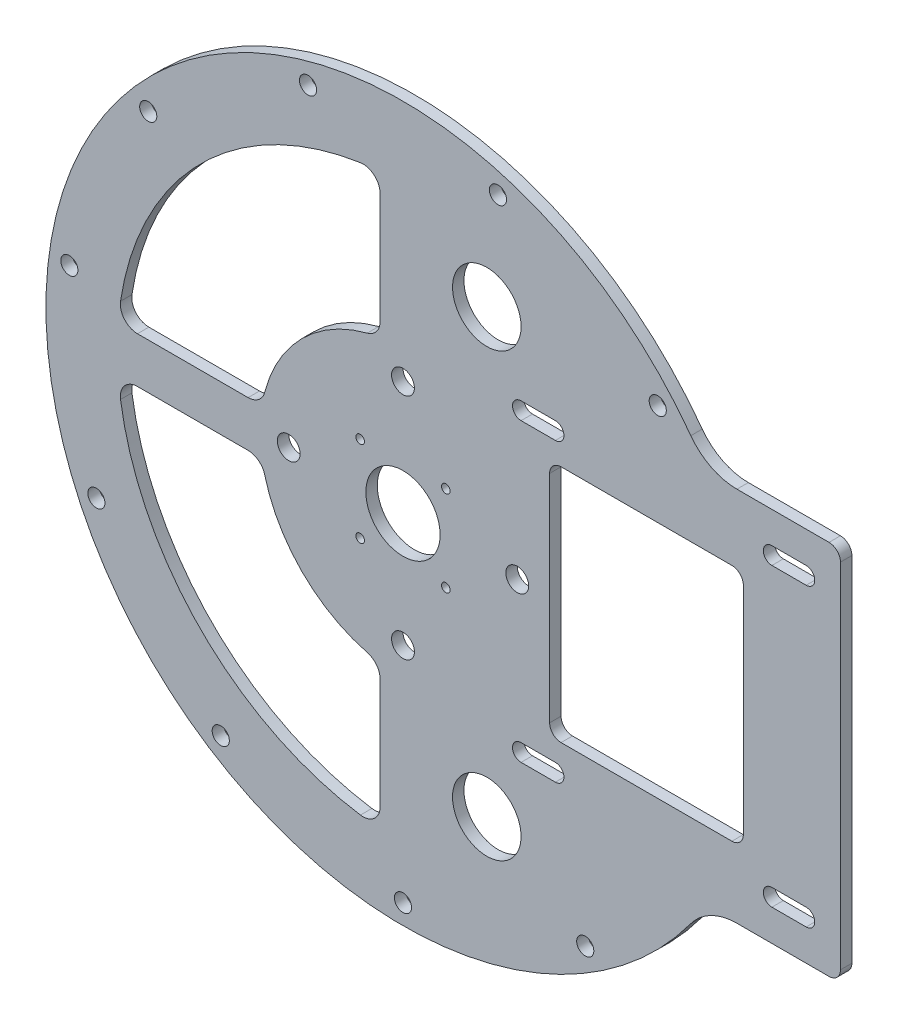
SolidWorks part; units mm, degrees
ref_plane "前视基准面" through (0, 0, 0) normal (0, 0, 1) x (1, 0, 0)
ref_plane "上视基准面" through (0, 0, 0) normal (0, 1, 0) x (1, 0, 0)
ref_plane "右视基准面" through (0, 0, 0) normal (1, 0, 0) x (0, 0, -1)
sketch "草图1" plane through (0, 0, 0) normal (0, 0, 1) x (1, 0, 0)
  line L0 (0, 0) -> (-27.6423, -27.6423) construction
  line L1 (0, 0) -> (0, -5.1352) construction
  line L2 (0, 0) -> (-102.4397, 0) construction
  line L3 (0, 1.2542) -> (0, 77.8801) construction
  line L4 (0, 0) -> (118.6635, 0) construction
  line L5 (0, 0) -> (0, -124.4057) construction
  line L6 (-46.4758, 4) -> (-27.1109, 4)
  line L8 (-27.1109, -4) -> (-46.4758, -4)
  line L9 (-4, 27.1109) -> (-4, 46.4758)
  line L12 (-4, -46.4758) -> (-4, -27.1109)
  line L14 (46.4758, -4) -> (27.1109, -4) [skipped]
  line L15 (4, -27.1109) -> (4, -46.4758) [skipped]
  line L16 (27.1109, 4) -> (46.4758, 4) [skipped]
  line L17 (4, 46.4758) -> (4, 27.1109) [skipped]
  line L19 (-14.6685, -17.526) -> (-14.6685, 17.526) construction
  line L20 (-14.6685, -17.526) -> (14.6685, -17.526) construction
  line L21 (14.6685, -17.526) -> (14.6685, 17.526) construction
  line L22 (-14.6685, 17.526) -> (14.6685, 17.526) construction
  line L24 (0, 0) -> (33.5645, 1.0745) construction
  line L25 (0, 0) -> (30.8589, 32.9) construction
  line L26 (14.6685, -9.5748) -> (14.6685, 9.5914) construction
  line L27 (-14.6685, -9.5748) -> (-14.6685, 9.5914) construction
  line L28 (14.6685, 28.961) -> (14.6685, -32.7618) construction
  line L29 (20.6685, 25.9) -> (64.5685, 25.9) construction
  line L30 (20.6685, 25.9) -> (20.6685, -25.9) construction
  line L31 (20.6685, -25.9) -> (64.5685, -25.9) construction
  line L32 (64.5685, 25.9) -> (64.5685, -25.9) construction
  line L33 (20.6685, -25.9) -> (26.6685, -25.9) construction
  line L34 (20.6685, -24.4) -> (26.6685, -24.4)
  line L35 (20.6685, -27.4) -> (26.6685, -27.4)
  line L36 (20.6685, 25.9) -> (26.6685, 25.9) construction
  line L37 (20.6685, 27.4) -> (26.6685, 27.4)
  line L38 (20.6685, 24.4) -> (26.6685, 24.4)
  line L39 (64.5685, 25.9) -> (70.5685, 25.9) construction
  line L40 (64.5685, 27.4) -> (70.5685, 27.4)
  line L41 (64.5685, 24.4) -> (70.5685, 24.4)
  line L42 (64.5685, -25.9) -> (70.5685, -25.9) construction
  line L43 (64.5685, -24.4) -> (70.5685, -24.4)
  line L44 (64.5685, -27.4) -> (70.5685, -27.4)
  line L45 (58.4452, 32.9) -> (74.5685, 32.9)
  line L46 (58.4452, -32.9) -> (74.5685, -32.9)
  line L47 (76.5685, -30.9) -> (76.5685, 30.9)
  line L48 (27.6685, 20.9) -> (57.5685, 20.9)
  line L49 (59.5685, 18.9) -> (59.5685, -18.9)
  line L50 (27.6685, -20.9) -> (57.5685, -20.9)
  line L51 (25.6685, 18.9) -> (25.6685, -18.9)
  line L52 (59.5685, 20.9) -> (59.5685, -20.9) construction
  line L53 (25.6685, -20.9) -> (59.5685, -20.9) construction
  line L54 (25.6685, 20.9) -> (59.5685, 20.9) construction
  line L55 (25.6685, 20.9) -> (25.6685, -20.9) construction
  circle A0 centre (0, 0) radius 59 construction
  circle A1 centre (0, 0) radius 20 construction
  circle A2 centre (0, 0) radius 62.5 construction
  circle A3 centre (0, -20) radius 2
  circle A4 centre (0, -59) radius 1.5
  circle A5 centre (-20, 0) radius 2
  circle A6 centre (0, 20) radius 2
  circle A7 centre (20, 0) radius 2
  circle A8 centre (-31.8978, -49.634) radius 1.5
  circle A9 centre (-53.6683, -24.5095) radius 1.5
  circle A10 centre (-58.3995, 8.3966) radius 1.5
  circle A11 centre (-44.5892, 38.6368) radius 1.5
  circle A12 centre (-16.6222, 56.6101) radius 1.5
  circle A13 centre (16.6222, 56.6101) radius 1.5
  circle A14 centre (44.5892, 38.6368) radius 1.5
  circle A15 centre (58.3995, 8.3966) radius 1.5 construction
  circle A16 centre (53.6683, -24.5095) radius 1.5 construction
  circle A17 centre (31.8978, -49.634) radius 1.5
  circle A18 centre (0, 0) radius 6.5
  circle A19 centre (0, 0) radius 10.6045 construction
  circle A21 centre (-7.4985, -7.4985) radius 0.75
  circle A22 centre (-7.4985, 7.4985) radius 0.75
  circle A23 centre (7.4985, 7.4985) radius 0.75
  circle A24 centre (7.4985, -7.4985) radius 0.75
  circle A25 centre (0, 0) radius 50 construction
  circle A26 centre (0, 0) radius 25 construction
  arc A27 (-49.4423, 7.4468) -> (-7.4468, 49.4423) centre (0, 0) cw
  arc A28 (-24.2061, 6.25) -> (-6.25, 24.2061) centre (0, 0) cw
  arc A33 (-6.25, -24.2061) -> (-24.2061, -6.25) centre (0, 0) cw
  arc A34 (-7.4468, -49.4423) -> (-49.4423, -7.4468) centre (0, 0) cw
  arc A43 (-6.25, -24.2061) -> (-4, -27.1109) centre (-7, -27.1109) cw
  arc A44 (-7.4468, -49.4423) -> (-4, -46.4758) centre (-7, -46.4758) ccw
  arc A45 (-24.2061, -6.25) -> (-27.1109, -4) centre (-27.1109, -7) ccw
  arc A46 (-49.4423, -7.4468) -> (-46.4758, -4) centre (-46.4758, -7) cw
  arc A47 (-27.1109, 4) -> (-24.2061, 6.25) centre (-27.1109, 7) ccw
  arc A48 (-6.25, 24.2061) -> (-4, 27.1109) centre (-7, 27.1109) ccw
  arc A49 (-4, 46.4758) -> (-7.4468, 49.4423) centre (-7, 46.4758) ccw
  arc A50 (-49.4423, 7.4468) -> (-46.4758, 4) centre (-46.4758, 7) ccw
  arc A51 (49.4423, -7.4468) -> (7.4468, -49.4423) centre (0, 0) cw [skipped]
  arc A52 (24.2061, -6.25) -> (6.25, -24.2061) centre (0, 0) cw [skipped]
  arc A53 (6.25, 24.2061) -> (24.2061, 6.25) centre (0, 0) cw [skipped]
  arc A54 (7.4468, 49.4423) -> (49.4423, 7.4468) centre (0, 0) cw [skipped]
  circle A55 centre (0, 0) radius 10.6045 construction
  circle A56 centre (0, 0) radius 17.526 construction
  circle A59 centre (7.2547, 7.7346) radius 1 construction
  circle A60 centre (-7.4985, -7.4985) radius 1 construction
  circle A61 centre (-7.4985, 7.4985) radius 1 construction
  arc A62 (-14.6685, -9.5748) -> (14.6685, -9.5748) centre (0, 0) ccw construction
  arc A63 (-14.6685, 9.5914) -> (14.6685, 9.5914) centre (0, 0) cw construction
  circle A64 centre (20.6685, 25.9) radius 1.5 construction
  circle A65 centre (64.5685, 25.9) radius 1.5 construction
  circle A66 centre (20.6685, -25.9) radius 1.5 construction
  circle A67 centre (64.5685, -25.9) radius 1.5 construction
  arc A68 (20.6685, -24.4) -> (20.6685, -27.4) centre (20.6685, -25.9) ccw
  arc A69 (26.6685, -27.4) -> (26.6685, -24.4) centre (26.6685, -25.9) ccw
  arc A70 (20.6685, 27.4) -> (20.6685, 24.4) centre (20.6685, 25.9) ccw
  arc A71 (26.6685, 24.4) -> (26.6685, 27.4) centre (26.6685, 25.9) ccw
  arc A72 (64.5685, 27.4) -> (64.5685, 24.4) centre (64.5685, 25.9) ccw
  arc A73 (70.5685, 24.4) -> (70.5685, 27.4) centre (70.5685, 25.9) ccw
  arc A74 (64.5685, -24.4) -> (64.5685, -27.4) centre (64.5685, -25.9) ccw
  arc A75 (70.5685, -27.4) -> (70.5685, -24.4) centre (70.5685, -25.9) ccw
  arc A76 (50.3838, 36.9828) -> (50.3838, -36.9828) centre (0, 0) ccw
  arc A77 (58.4452, 32.9) -> (50.3838, 36.9828) centre (58.4452, 42.9) cw
  arc A78 (58.4452, -32.9) -> (50.3838, -36.9828) centre (58.4452, -42.9) ccw
  circle A79 centre (14.6685, 38.6368) radius 6
  circle A80 centre (14.6685, -38.6368) radius 6
  arc A81 (59.5685, -18.9) -> (57.5685, -20.9) centre (57.5685, -18.9) cw
  arc A82 (59.5685, 18.9) -> (57.5685, 20.9) centre (57.5685, 18.9) ccw
  arc A83 (27.6685, 20.9) -> (25.6685, 18.9) centre (27.6685, 18.9) ccw
  arc A84 (25.6685, -18.9) -> (27.6685, -20.9) centre (27.6685, -18.9) ccw
  arc A85 (74.5685, -32.9) -> (76.5685, -30.9) centre (74.5685, -30.9) ccw
  arc A86 (74.5685, 32.9) -> (76.5685, 30.9) centre (74.5685, 30.9) cw
  point P94 (-24.6779, -4)
  point P97 (-49.8397, -4)
  point P100 (-24.6779, 4)
  point P107 (-49.8397, 4)
  point P129 (23.6685, -25.9)
  point P136 (23.6685, 25.9)
  point P143 (67.5685, 25.9)
  point P150 (67.5685, -25.9)
  point P160 (66.5068, -32.9)
  point P164 (53.1398, 32.9)
  point P166 (53.1398, -32.9)
  dimension "D1" = 125
  dimension "D2" = 118
  dimension "D3" = 40
  dimension "D4" = 4
  dimension "D5" = 3
  dimension "D8" = 13
  dimension "D9" = 21.209
  dimension "D10" = 1.5
  dimension "D12" = 4
  dimension "D14" = 50
  dimension "D15" = 100
  dimension "D17" = 4
  dimension "D18" = 21.209
  dimension "D19" = 43.9
  dimension "D26" = 3
  dimension "D27" = 3
  dimension "D28" = 3
  dimension "D29" = 3
  dimension "D31" = 12
  dimension "D34" = 10
  dimension "D36" = 2
  dimension "D11" = 4
  dimension "D13" = 4
  dimension "D20" = 29.337
  dimension "D21" = 14.6685
  dimension "D22" = 35.052
  dimension "D23" = 17.526
  dimension "D24" = 45
  dimension "D25" = 51.8
  dimension "D30" = 6
  dimension "D32" = 7
  dimension "D33" = 7
  dimension "D35" = 5
  dimension "D6" = 4
  dimension "D7" = 11
  dimension "D16" = 4
extrude "凸台-拉伸1" add sketch "草图1" along normal blind 2 contours A2
